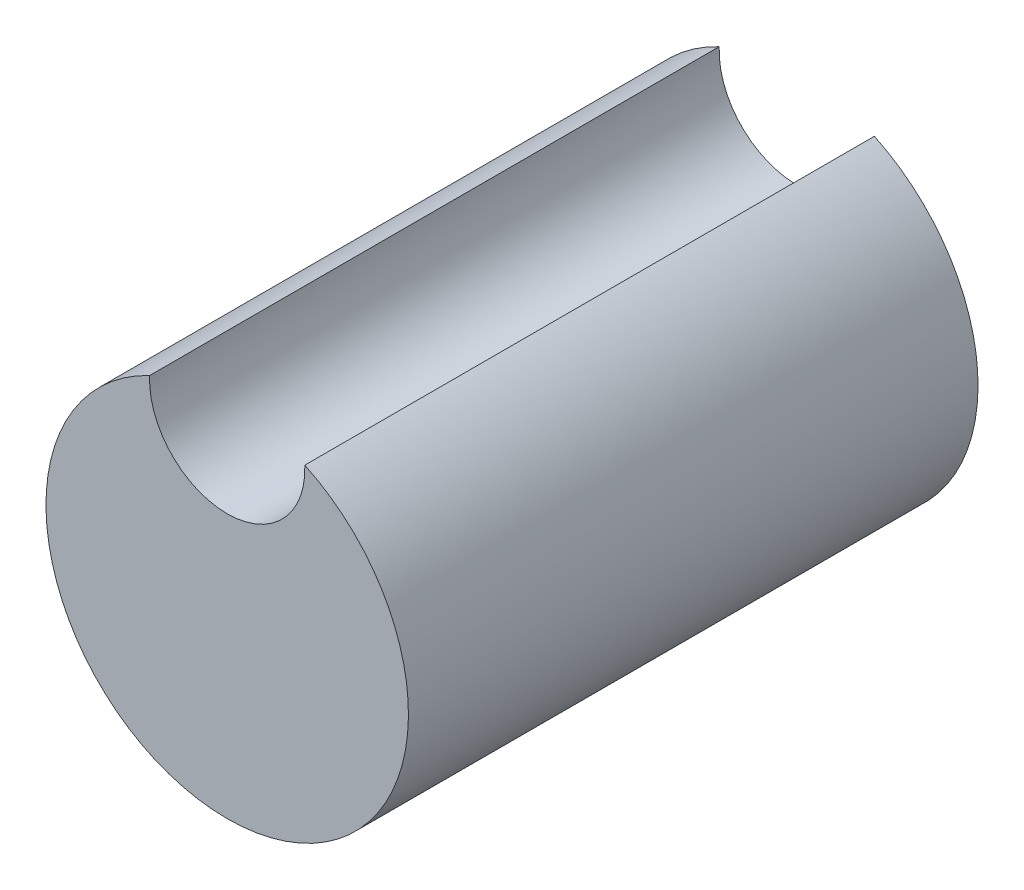
SolidWorks part; units mm, degrees
ref_plane "Plan de face" through (0, 0, 0) normal (0, 0, 1) x (1, 0, 0)
ref_plane "Plan de dessus" through (0, 0, 0) normal (0, 1, 0) x (1, 0, 0)
ref_plane "Plan de droite" through (0, 0, 0) normal (1, 0, 0) x (0, 0, -1)
sketch "Esquisse3" plane through (0, 0, 0) normal (0, 0, 1) x (1, 0, 0)
  circle A0 centre (0, 0) radius 17.5
  dimension "D1" = 35
extrude "Extrusion2" add sketch "Esquisse3" along normal blind 55
sketch "Esquisse4" plane through (0, 0, 55) normal (0, 0, 1) x (1, 0, 0)
  line L0 (-7.5, 15.5) -> (7.5, 15.5) construction
  line L1 (0, 15.5) -> (0, 17.5) construction
  circle A1 centre (0, 15.5) radius 7.5
  circle A4 centre (0, 0) radius 17.5 construction
  dimension "D1" = 15
  dimension "D2" = 2
extrude "Extrusion4" cut sketch "Esquisse4" against normal up to next
